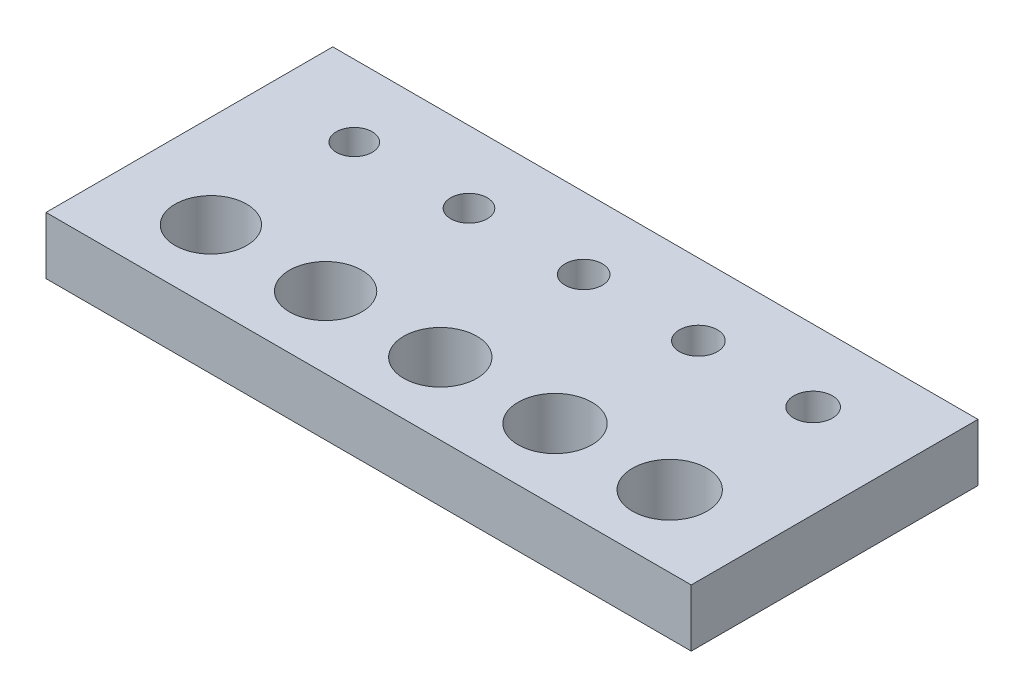
SolidWorks part; units mm, degrees
ref_plane "Front Plane" through (0, 0, 0) normal (0, 0, 1) x (1, 0, 0)
ref_plane "Top Plane" through (0, 0, 0) normal (0, 1, 0) x (1, 0, 0)
ref_plane "Right Plane" through (0, 0, 0) normal (1, 0, 0) x (0, 0, -1)
sketch "Sketch1" plane through (0, 0, 0) normal (0, 1, 0) x (1, 0, 0)
  line L1 (45, -20) -> (-45, -20)
  line L2 (45, -20) -> (45, 20)
  line L3 (45, 20) -> (-45, 20)
  line L4 (-45, -20) -> (-45, 20)
  line L5 (45, -20) -> (-45, 20) construction
  line L6 (45, 20) -> (-45, -20) construction
  point P0 (0, 0)
  dimension "D1" = 90
  dimension "D2" = 40
extrude "Plate" add sketch "Sketch1" along normal blind 8
sketch "Sketch2" plane through (0, 8, 0) normal (0, 1, 0) x (1, 0, 0)
  circle A0 centre (-32, 10) radius 2.5
  circle A1 centre (-16, 10) radius 2.55
  circle A2 centre (0, 10) radius 2.6
  circle A3 centre (16, 10) radius 2.65
  circle A4 centre (32, 10) radius 2.7
  circle A5 centre (-32, -10) radius 5
  circle A6 centre (-16, -10) radius 5.05
  circle A7 centre (0, -10) radius 5.1
  circle A8 centre (16, -10) radius 5.15
  circle A9 centre (32, -10) radius 5.2
  point P20 (0, 0)
  point P21 (0, 0)
  point P22 (0, 0)
  point P23 (0, 0)
  point P24 (0, 0)
  point P25 (0, 0)
  point P26 (0, 0)
  point P27 (0, 0)
  point P28 (0, 0)
  point P29 (0, 0)
  point P30 (0, 0)
  point P31 (0, 0)
  point P32 (0, 0)
  point P33 (0, 0)
  point P34 (0, 0)
  point P35 (0, 0)
  point P37 (0, 0)
  point P38 (0, 0)
  point P39 (0, 0)
  dimension "D1" = 5
  dimension "D2" = 5.1
  dimension "D3" = 5.2
  dimension "D4" = 5.3
  dimension "D5" = 5.4
  dimension "D6" = 10
  dimension "D7" = 10.1
  dimension "D8" = 10.2
  dimension "D9" = 10.3
  dimension "D10" = 10.4
  dimension "D11" = 10
  dimension "D12" = 10
  dimension "D13" = 16
  dimension "D14" = 16
  dimension "D15" = 16
  dimension "D16" = 16
  dimension "D17" = 16
  dimension "D18" = 16
  dimension "D19" = 16
  dimension "D20" = 16
extrude "Test holes" cut sketch "Sketch2" against normal through all
chamfer "Bed chamfers" distance 0.5 angle 45 10 edges at (-32, 0, -7.5) (-16, 0, -7.45) (0, 0, -7.4) (16, 0, -7.35) (32, 0, -7.3) (32, 0, 15.2) (16, 0, 15.15) (0, 0, 15.1) (-16, 0, 15.05) (-32, 0, 15)
